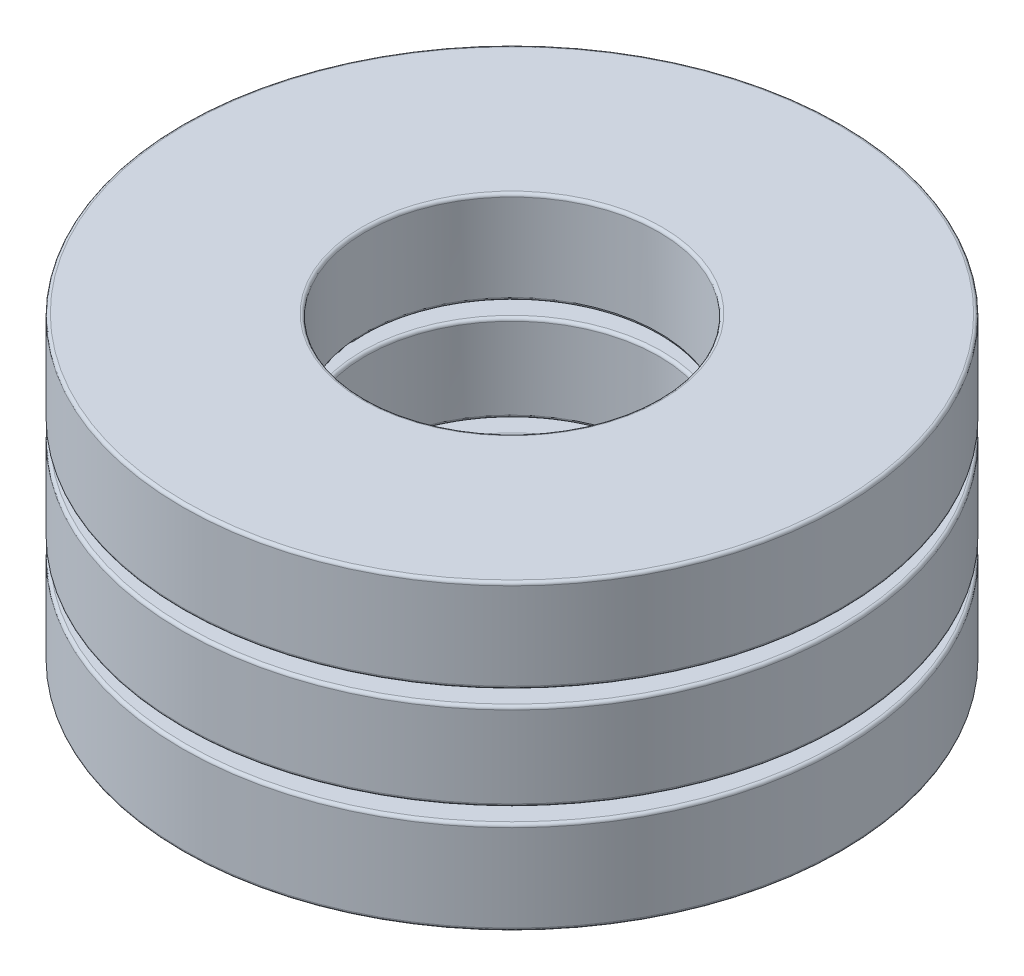
SolidWorks part; units mm, degrees
other "Imported5"
other "Imported4"
other "Imported3"
other "Imported1"
other "Imported2"
other "Imported8"
other "Imported6"
other "Imported7"
other "Imported9" parameters "Angle"=60, "Balls"=6, "D1"=6, "D2"=60, "OD"=28, "Shaft Dia"=8.0137, "Th"=8.74, "D3"=4.9022, "ID"=16.076, "E | Thickness"=4.92, "Thickness"=4.13, "Washer Thickness"=1.27, "F | Ball Diameter"=2, "Ball Diameter"=2
ref_plane "Front Plane" through (0, 0, 0) normal (0, 0, 1) x (1, 0, 0)
ref_plane "Top Plane" through (0, 0, 0) normal (0, 1, 0) x (1, 0, 0)
ref_plane "Right Plane" through (0, 0, 0) normal (1, 0, 0) x (0, 0, -1)
sketch "Sketch1" plane through (0, 0, 0) normal (0, 1, 0) x (1, 0, 0)
  circle A0 centre (0, 0) radius 4.5 construction
  circle A1 centre (0, 0) radius 2.005 construction
  circle A2 centre (0, 0) radius 3.25 construction
  dimension "OD" = 9
  dimension "Ball Circle" = 6.5
  dimension "ID" = 4.01
sketch "Sketch2" plane through (0, 0, 0) normal (0, 0, -1) x (-1, 0, 0)
  line L0 (-4.5, 2.065) -> (-4.5, 0.795) construction
  line L1 (-4.5, 0) -> (0, 0) construction
  line L3 (0, 2.065) -> (0, -2.065) construction
  line L4 (-4.5, 0.795) -> (-4.5, -0.795) construction
  line L6 (-4.5, -0.795) -> (-4.5, -2.065) construction
  point P11 (-4.5, 0)
sketch "Sketch3" plane through (0, 0, 0) normal (0, 0, 1) x (1, 0, 0)
  line L2 (4.5, 0.5962) -> (2.005, 0.5962)
  line L4 (4.5, 0.5962) -> (4.5, -0.5963)
  line L7 (4.5, -0.5963) -> (2.005, -0.5963)
  line L8 (2.005, 0.5962) -> (2.005, -0.5963)
  line L11 (4.5, 0.795) -> (4.5, -0.795) construction
  point P8 (2.005, 0)
  dimension "D1" = 1.1925
revolve "Revolve1" add sketch "Sketch3" angle 360 about L3
sketch "Sketch4" plane through (0, 0, 0) normal (0, 0, 1) x (1, 0, 0)
  line L0 (3.25, 0.795) -> (3.25, -0.795)
  arc A0 (3.25, 0.795) -> (3.25, -0.795) centre (3.25, 0) ccw
revolve "Cut-Revolve1" cut sketch "Sketch4" angle 360 about L0
sketch "Sketch5" plane through (0, 0, 0) normal (0, 0, 1) x (1, 0, 0)
  line L0 (3.25, 0.795) -> (3.25, -0.795)
  arc A0 (3.25, 0.795) -> (3.25, -0.795) centre (3.25, 0) ccw
revolve "Revolve2" add sketch "Sketch5" angle 360 about L0
pattern_circular "CirPattern1" count 6 every 60 about axis through (0, 2.065, 0) along (0, -1, 0) of bodies 187
pattern_circular "CirPattern2" count 6 every 60 about axis through (0, 0, 0) along (0, 1, 0) of "Cut-Revolve1"
sketch "Sketch6" plane through (0, 0, 0) normal (0, 0, 1) x (1, 0, 0)
  line L2 (4.5, 2.065) -> (2.005, 2.065)
  line L3 (4.5, 2.065) -> (4.5, 0.795)
  line L4 (4.5, 0.795) -> (2.005, 0.795)
  line L5 (2.005, 2.065) -> (2.005, 0.795)
  line L6 (4.5, -0.795) -> (2.005, -0.795)
  line L7 (4.5, -0.795) -> (4.5, -2.065)
  line L8 (4.5, -2.065) -> (2.005, -2.065)
  line L13 (2.005, -0.795) -> (2.005, -2.065)
  point P11 (2.005, 0)
revolve "Revolve3" add sketch "Sketch6" angle 360 about L3
fillet "Fillet1" radius 0.0413 4 edges at (0, 0.795, 2.005) (0, 0.795, 4.5) (0, 2.065, 4.5) (0, 2.065, 2.005)
fillet "Fillet2" radius 0.0413 16 edges at (0, -0.5963, 2.005) (0, -0.5962, 4.5) (3.25, -0.5963, 0.5258) (1.1696, -0.5963, 3.0775) (-2.0804, -0.5963, 2.5517) (-3.25, -0.5963, -0.5258) (-1.1696, -0.5963, -3.0775) (2.0804, -0.5963, -2.5517) (0, 0.5962, 4.5) (0, 0.5962, 2.005) (3.25, 0.5962, -0.5258) (2.0804, 0.5962, 2.5517) (-1.1696, 0.5962, 3.0775) (-3.25, 0.5962, 0.5258) (-2.0804, 0.5962, -2.5517) (1.1696, 0.5962, -3.0775)
fillet "Fillet3" radius 0.0413 4 edges at (0, -0.795, 4.5) (0, -0.795, 2.005) (0, -2.065, 2.005) (0, -2.065, 4.5)
equation "\"Angle@CirPattern1\" = 360/\"Balls@CirPattern1\""
equation "\"D1@CirPattern2\" = \"Balls@CirPattern1\""
equation "\"D2@CirPattern2\" = \"Angle@CirPattern1\""
equation "\"D1@Sketch3\" =  ( \"Thickness@Sketch2\" -  ( 2 * \"Washer Thickness@Sketch2\" )  )  * .75"
equation "\"D1@Fillet1\" = \"Thickness@Sketch2\" * .01"
equation "\"D1@Fillet2\"=\"D1@Fillet1\""
equation "\"D1@Fillet3\"=\"D1@Fillet1\""
